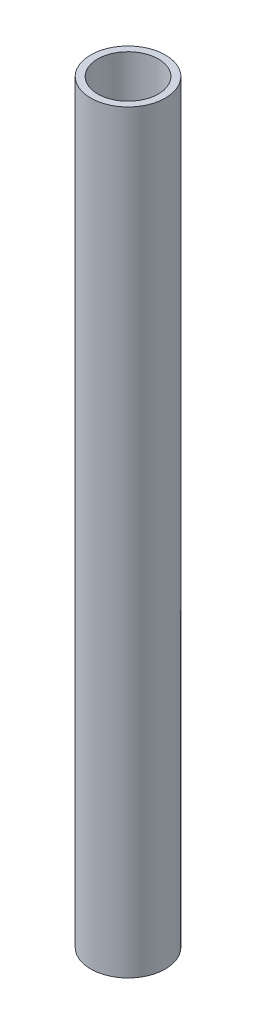
SolidWorks part; units mm, degrees
material "СТ3КП"
ref_plane "Спереди" through (0, 0, 0) normal (0, 0, 1) x (1, 0, 0)
ref_plane "Сверху" through (0, 0, 0) normal (0, 1, 0) x (1, 0, 0)
ref_plane "Справа" through (0, 0, 0) normal (1, 0, 0) x (0, 0, -1)
sketch "Эскиз1" plane through (0, 0, 0) normal (0, 1, 0) x (1, 0, 0)
  line L0 (0, 200914.2922) -> (0, -249007.8193) construction
  line L1 (-130, 9.15) -> (130, 9.15) construction
  circle B0 centre (0, -1.5) radius 8.65
  circle B1 centre (0, -1.5) radius 10.65
sketch_block_instance "Труба 21_3х2 1_2-1"
sketch_block "Труба 21_3х2 1_2" parameters "D2"=21.3, "D1"=2
extrude "Бобышка-Вытянуть1" add sketch "Эскиз1" along normal up to vertex (215 mm away)
